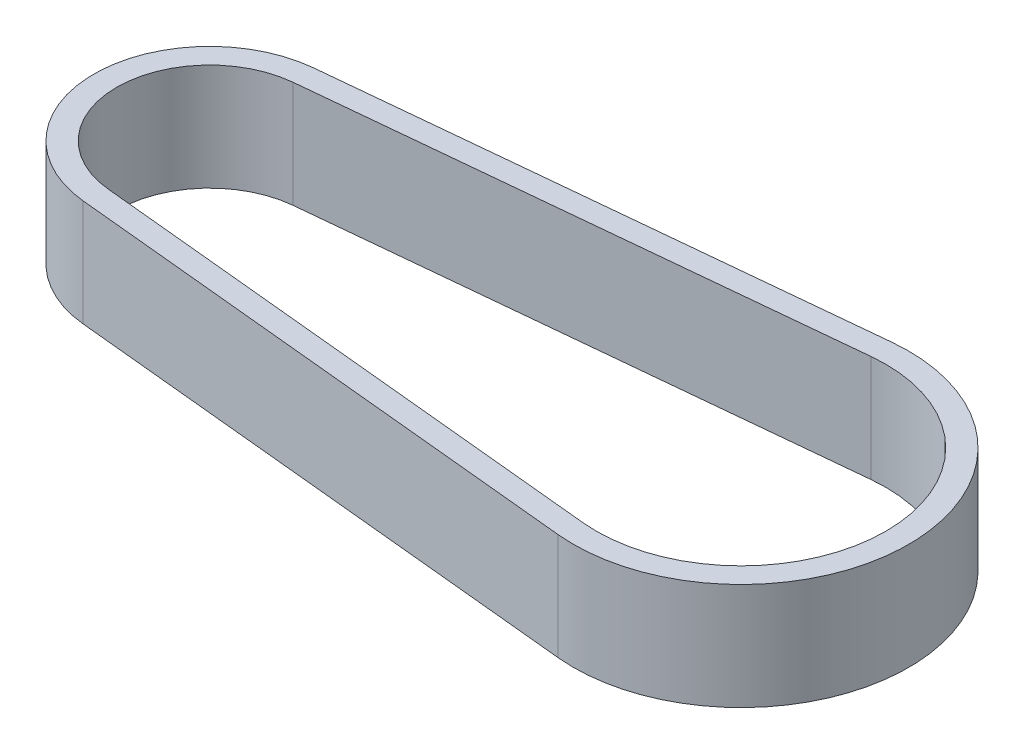
SolidWorks part; units mm, degrees
ref_plane "Front Plane" through (0, 0, 0) normal (0, 0, 1) x (1, 0, 0)
ref_plane "Top Plane" through (0, 0, 0) normal (0, 1, 0) x (1, 0, 0)
ref_plane "Right Plane" through (0, 0, 0) normal (1, 0, 0) x (0, 0, -1)
sketch "Sketch1" plane through (0, 0, 0) normal (0, 1, 0) x (1, 0, 0)
  line L0 (0, 0) -> (34.9, 0) construction
  line L1 (-0.5943, 6.071) -> (33.9745, 9.4548)
  line L2 (-0.5943, -6.071) -> (33.9745, -9.4548)
  line L3 (-0.7404, 7.5638) -> (33.8284, 10.9477)
  line L4 (-0.7404, -7.5638) -> (33.8284, -10.9477)
  arc A0 (-0.5943, 6.071) -> (-0.5943, -6.071) centre (0, 0) ccw
  arc A1 (33.9745, -9.4548) -> (33.9745, 9.4548) centre (34.9, 0) ccw
  arc A2 (33.8284, -10.9477) -> (33.8284, 10.9477) centre (34.9, 0) ccw
  arc A3 (-0.7404, 7.5638) -> (-0.7404, -7.5638) centre (0, 0) ccw
  dimension "D1" = 12.2
  dimension "D2" = 19
  dimension "D3" = 1.5
  dimension "D4" = 34.9
extrude "Boss-Extrude1" add sketch "Sketch1" along normal blind 7
